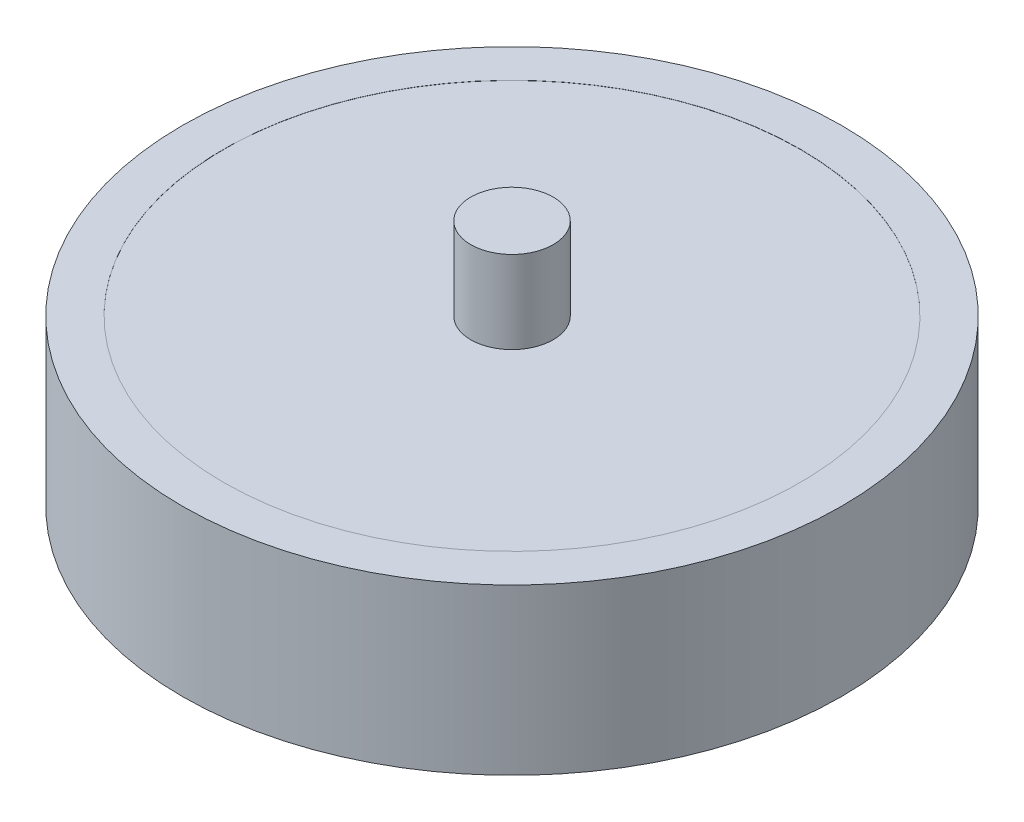
SolidWorks part; units mm, degrees
ref_plane "Front Plane" through (0, 0, 0) normal (0, 0, 1) x (1, 0, 0)
ref_plane "Top Plane" through (0, 0, 0) normal (0, 1, 0) x (1, 0, 0)
ref_plane "Right Plane" through (0, 0, 0) normal (1, 0, 0) x (0, 0, -1)
sketch "Sketch1" plane through (0, 0, 0) normal (0, 1, 0) x (1, 0, 0)
  circle A0 centre (0, 0) radius 20
  circle A1 centre (0, 0) radius 17.5
  dimension "D1" = 40
  dimension "D2" = 35
extrude "Boss-Extrude1" add sketch "Sketch1" along normal blind 10
sketch "Sketch2" plane through (0, 0, 0) normal (0, 1, 0) x (1, 0, 0)
  circle A0 centre (0, 0) radius 17.5
  dimension "D1" = 35
extrude "Boss-Extrude3" add sketch "Sketch2" along normal blind 9.99 separate body
sketch "Sketch3" plane through (0, 0, 0) normal (0, -1, 0) x (1, 0, 0)
  circle A0 centre (0, 0) radius 2.5
  dimension "D1" = 5
sketch "Sketch4" plane through (0, 9.99, 0) normal (0, 1, 0) x (1, 0, 0)
  circle A0 centre (0, 0) radius 2.5
  dimension "D1" = 5
extrude "Boss-Extrude4" add sketch "Sketch4" along normal blind 5
extrude "Cut-Extrude2" cut sketch "Sketch3" against normal blind 5 contours A0
